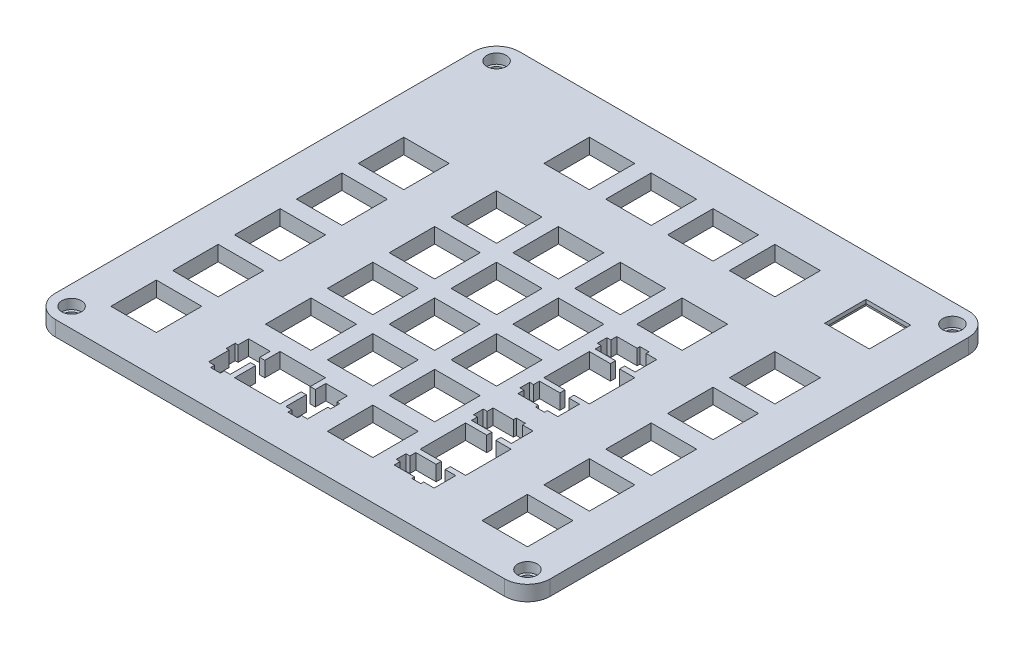
SolidWorks part; units mm, degrees
material "ABS"
ref_plane "Front Plane" through (0, 0, 0) normal (0, 0, 1) x (1, 0, 0)
ref_plane "Top Plane" through (0, 0, 0) normal (0, 1, 0) x (1, 0, 0)
ref_plane "Right Plane" through (0, 0, 0) normal (1, 0, 0) x (0, 0, -1)
sketch "Sketch6" plane through (0, 0, 0) normal (0, 1, 0) x (1, 0, 0)
  line L0 (7, 0) -> (145.39, 0)
  line L1 (152.39, 7) -> (152.39, 135.87)
  line L2 (7, 142.87) -> (145.39, 142.87)
  line L3 (0, 135.87) -> (0, 7)
  line L4 (54.62, 130.825) -> (40.62, 130.825)
  line L5 (40.62, 130.825) -> (40.62, 116.825)
  line L6 (40.62, 116.825) -> (54.62, 116.825)
  line L7 (54.62, 116.825) -> (54.62, 130.825)
  line L8 (73.67, 130.825) -> (59.67, 130.825)
  line L9 (59.67, 130.825) -> (59.67, 116.825)
  line L10 (59.67, 116.825) -> (73.67, 116.825)
  line L11 (73.67, 116.825) -> (73.67, 130.825)
  line L12 (92.72, 130.825) -> (78.72, 130.825)
  line L13 (78.72, 130.825) -> (78.72, 116.825)
  line L14 (78.72, 116.825) -> (92.72, 116.825)
  line L15 (92.72, 116.825) -> (92.72, 130.825)
  line L16 (111.77, 130.825) -> (97.77, 130.825)
  line L17 (97.77, 130.825) -> (97.77, 116.825)
  line L18 (97.77, 116.825) -> (111.77, 116.825)
  line L19 (111.77, 116.825) -> (111.77, 130.825)
  line L20 (26.045, 102.25) -> (12.045, 102.25)
  line L21 (12.045, 102.25) -> (12.045, 88.25)
  line L22 (12.045, 88.25) -> (26.045, 88.25)
  line L23 (26.045, 88.25) -> (26.045, 102.25)
  line L24 (54.62, 102.25) -> (40.62, 102.25)
  line L25 (40.62, 102.25) -> (40.62, 88.25)
  line L26 (40.62, 88.25) -> (54.62, 88.25)
  line L27 (54.62, 88.25) -> (54.62, 102.25)
  line L28 (73.67, 102.25) -> (59.67, 102.25)
  line L29 (59.67, 102.25) -> (59.67, 88.25)
  line L30 (59.67, 88.25) -> (73.67, 88.25)
  line L31 (73.67, 88.25) -> (73.67, 102.25)
  line L32 (92.72, 102.25) -> (78.72, 102.25)
  line L33 (78.72, 102.25) -> (78.72, 88.25)
  line L34 (78.72, 88.25) -> (92.72, 88.25)
  line L35 (92.72, 88.25) -> (92.72, 102.25)
  line L36 (111.77, 102.25) -> (97.77, 102.25)
  line L37 (97.77, 102.25) -> (97.77, 88.25)
  line L38 (97.77, 88.25) -> (111.77, 88.25)
  line L39 (111.77, 88.25) -> (111.77, 102.25)
  line L40 (140.345, 102.25) -> (126.345, 102.25)
  line L41 (126.345, 102.25) -> (126.345, 88.25)
  line L42 (126.345, 88.25) -> (140.345, 88.25)
  line L43 (140.345, 88.25) -> (140.345, 102.25)
  line L44 (26.045, 83.2) -> (12.045, 83.2)
  line L45 (12.045, 83.2) -> (12.045, 69.2)
  line L46 (12.045, 69.2) -> (26.045, 69.2)
  line L47 (26.045, 69.2) -> (26.045, 83.2)
  line L48 (54.62, 83.2) -> (40.62, 83.2)
  line L49 (40.62, 83.2) -> (40.62, 69.2)
  line L50 (40.62, 69.2) -> (54.62, 69.2)
  line L51 (54.62, 69.2) -> (54.62, 83.2)
  line L52 (73.67, 83.2) -> (59.67, 83.2)
  line L53 (59.67, 83.2) -> (59.67, 69.2)
  line L54 (59.67, 69.2) -> (73.67, 69.2)
  line L55 (73.67, 69.2) -> (73.67, 83.2)
  line L56 (92.72, 83.2) -> (78.72, 83.2)
  line L57 (78.72, 83.2) -> (78.72, 69.2)
  line L58 (78.72, 69.2) -> (92.72, 69.2)
  line L59 (92.72, 69.2) -> (92.72, 83.2)
  line L60 (98, 77.075) -> (98, 75.25)
  line L61 (98, 75.25) -> (104.27, 75.25)
  line L62 (104.27, 75.25) -> (104.27, 73.675)
  line L63 (104.27, 73.675) -> (97.77, 73.675)
  line L64 (97.77, 73.675) -> (97.77, 59.675)
  line L65 (97.77, 59.675) -> (104.27, 59.675)
  line L66 (104.27, 59.675) -> (104.27, 58.1)
  line L67 (104.27, 58.1) -> (98, 58.1)
  line L68 (98, 58.1) -> (98, 56.275)
  line L69 (98, 56.275) -> (96.8, 56.275)
  line L70 (96.8, 56.275) -> (96.8, 53.275)
  line L71 (96.8, 53.275) -> (98, 53.275)
  line L72 (98, 53.275) -> (98, 51.45)
  line L73 (98, 51.45) -> (104.27, 51.45)
  line L74 (104.27, 51.45) -> (104.27, 50.575)
  line L75 (104.27, 50.575) -> (107.07, 50.575)
  line L76 (107.07, 50.575) -> (107.07, 51.45)
  line L77 (107.07, 51.45) -> (110.3, 51.45)
  line L78 (110.3, 51.45) -> (110.3, 58.1)
  line L79 (110.3, 58.1) -> (107.07, 58.1)
  line L80 (107.07, 58.1) -> (107.07, 59.675)
  line L81 (107.07, 59.675) -> (111.77, 59.675)
  line L82 (111.77, 59.675) -> (111.77, 73.675)
  line L83 (111.77, 73.675) -> (107.07, 73.675)
  line L84 (107.07, 73.675) -> (107.07, 75.25)
  line L85 (107.07, 75.25) -> (110.3, 75.25)
  line L86 (110.3, 75.25) -> (110.3, 81.9)
  line L87 (110.3, 81.9) -> (107.07, 81.9)
  line L88 (107.07, 81.9) -> (107.07, 82.775)
  line L89 (107.07, 82.775) -> (104.27, 82.775)
  line L90 (104.27, 82.775) -> (104.27, 81.9)
  line L91 (104.27, 81.9) -> (98, 81.9)
  line L92 (98, 81.9) -> (98, 80.075)
  line L93 (98, 80.075) -> (96.8, 80.075)
  line L94 (96.8, 80.075) -> (96.8, 77.075)
  line L95 (96.8, 77.075) -> (98, 77.075)
  line L96 (140.345, 83.2) -> (126.345, 83.2)
  line L97 (126.345, 83.2) -> (126.345, 69.2)
  line L98 (126.345, 69.2) -> (140.345, 69.2)
  line L99 (140.345, 69.2) -> (140.345, 83.2)
  line L100 (26.045, 64.15) -> (12.045, 64.15)
  line L101 (12.045, 64.15) -> (12.045, 50.15)
  line L102 (12.045, 50.15) -> (26.045, 50.15)
  line L103 (26.045, 50.15) -> (26.045, 64.15)
  line L104 (54.62, 64.15) -> (40.62, 64.15)
  line L105 (40.62, 64.15) -> (40.62, 50.15)
  line L106 (40.62, 50.15) -> (54.62, 50.15)
  line L107 (54.62, 50.15) -> (54.62, 64.15)
  line L108 (73.67, 64.15) -> (59.67, 64.15)
  line L109 (59.67, 64.15) -> (59.67, 50.15)
  line L110 (59.67, 50.15) -> (73.67, 50.15)
  line L111 (73.67, 50.15) -> (73.67, 64.15)
  line L112 (92.72, 64.15) -> (78.72, 64.15)
  line L113 (78.72, 64.15) -> (78.72, 50.15)
  line L114 (78.72, 50.15) -> (92.72, 50.15)
  line L115 (92.72, 50.15) -> (92.72, 64.15)
  line L116 (140.345, 64.15) -> (126.345, 64.15)
  line L117 (126.345, 64.15) -> (126.345, 50.15)
  line L118 (126.345, 50.15) -> (140.345, 50.15)
  line L119 (140.345, 50.15) -> (140.345, 64.15)
  line L120 (26.045, 45.1) -> (12.045, 45.1)
  line L121 (12.045, 45.1) -> (12.045, 31.1)
  line L122 (12.045, 31.1) -> (26.045, 31.1)
  line L123 (26.045, 31.1) -> (26.045, 45.1)
  line L124 (54.62, 45.1) -> (40.62, 45.1)
  line L125 (40.62, 45.1) -> (40.62, 31.1)
  line L126 (40.62, 31.1) -> (54.62, 31.1)
  line L127 (54.62, 31.1) -> (54.62, 45.1)
  line L128 (73.67, 45.1) -> (59.67, 45.1)
  line L129 (59.67, 45.1) -> (59.67, 31.1)
  line L130 (59.67, 31.1) -> (73.67, 31.1)
  line L131 (73.67, 31.1) -> (73.67, 45.1)
  line L132 (92.72, 45.1) -> (78.72, 45.1)
  line L133 (78.72, 45.1) -> (78.72, 31.1)
  line L134 (78.72, 31.1) -> (92.72, 31.1)
  line L135 (92.72, 31.1) -> (92.72, 45.1)
  line L136 (98, 38.975) -> (98, 37.15)
  line L137 (98, 37.15) -> (104.27, 37.15)
  line L138 (104.27, 37.15) -> (104.27, 35.575)
  line L139 (104.27, 35.575) -> (97.77, 35.575)
  line L140 (97.77, 35.575) -> (97.77, 21.575)
  line L141 (97.77, 21.575) -> (104.27, 21.575)
  line L142 (104.27, 21.575) -> (104.27, 20)
  line L143 (104.27, 20) -> (98, 20)
  line L144 (98, 20) -> (98, 18.175)
  line L145 (98, 18.175) -> (96.8, 18.175)
  line L146 (96.8, 18.175) -> (96.8, 15.175)
  line L147 (96.8, 15.175) -> (98, 15.175)
  line L148 (98, 15.175) -> (98, 13.35)
  line L149 (98, 13.35) -> (104.27, 13.35)
  line L150 (104.27, 13.35) -> (104.27, 12.475)
  line L151 (104.27, 12.475) -> (107.07, 12.475)
  line L152 (107.07, 12.475) -> (107.07, 13.35)
  line L153 (107.07, 13.35) -> (110.3, 13.35)
  line L154 (110.3, 13.35) -> (110.3, 20)
  line L155 (110.3, 20) -> (107.07, 20)
  line L156 (107.07, 20) -> (107.07, 21.575)
  line L157 (107.07, 21.575) -> (111.77, 21.575)
  line L158 (111.77, 21.575) -> (111.77, 35.575)
  line L159 (111.77, 35.575) -> (107.07, 35.575)
  line L160 (107.07, 35.575) -> (107.07, 37.15)
  line L161 (107.07, 37.15) -> (110.3, 37.15)
  line L162 (110.3, 37.15) -> (110.3, 43.8)
  line L163 (110.3, 43.8) -> (107.07, 43.8)
  line L164 (107.07, 43.8) -> (107.07, 44.675)
  line L165 (107.07, 44.675) -> (104.27, 44.675)
  line L166 (104.27, 44.675) -> (104.27, 43.8)
  line L167 (104.27, 43.8) -> (98, 43.8)
  line L168 (98, 43.8) -> (98, 41.975)
  line L169 (98, 41.975) -> (96.8, 41.975)
  line L170 (96.8, 41.975) -> (96.8, 38.975)
  line L171 (96.8, 38.975) -> (98, 38.975)
  line L172 (140.345, 45.1) -> (126.345, 45.1)
  line L173 (126.345, 45.1) -> (126.345, 31.1)
  line L174 (126.345, 31.1) -> (140.345, 31.1)
  line L175 (140.345, 31.1) -> (140.345, 45.1)
  line L176 (26.045, 26.05) -> (12.045, 26.05)
  line L177 (12.045, 26.05) -> (12.045, 12.05)
  line L178 (12.045, 12.05) -> (26.045, 12.05)
  line L179 (26.045, 12.05) -> (26.045, 26.05)
  line L180 (46.745, 12.28) -> (48.57, 12.28)
  line L181 (48.57, 12.28) -> (48.57, 18.55)
  line L182 (48.57, 18.55) -> (50.145, 18.55)
  line L183 (50.145, 18.55) -> (50.145, 12.05)
  line L184 (50.145, 12.05) -> (64.145, 12.05)
  line L185 (64.145, 12.05) -> (64.145, 18.55)
  line L186 (64.145, 18.55) -> (65.72, 18.55)
  line L187 (65.72, 18.55) -> (65.72, 12.28)
  line L188 (65.72, 12.28) -> (67.545, 12.28)
  line L189 (67.545, 12.28) -> (67.545, 11.08)
  line L190 (67.545, 11.08) -> (70.545, 11.08)
  line L191 (70.545, 11.08) -> (70.545, 12.28)
  line L192 (70.545, 12.28) -> (72.37, 12.28)
  line L193 (72.37, 12.28) -> (72.37, 18.55)
  line L194 (72.37, 18.55) -> (73.245, 18.55)
  line L195 (73.245, 18.55) -> (73.245, 21.35)
  line L196 (73.245, 21.35) -> (72.37, 21.35)
  line L197 (72.37, 21.35) -> (72.37, 24.58)
  line L198 (72.37, 24.58) -> (65.72, 24.58)
  line L199 (65.72, 24.58) -> (65.72, 21.35)
  line L200 (65.72, 21.35) -> (64.145, 21.35)
  line L201 (64.145, 21.35) -> (64.145, 26.05)
  line L202 (64.145, 26.05) -> (50.145, 26.05)
  line L203 (50.145, 26.05) -> (50.145, 21.35)
  line L204 (50.145, 21.35) -> (48.57, 21.35)
  line L205 (48.57, 21.35) -> (48.57, 24.58)
  line L206 (48.57, 24.58) -> (41.92, 24.58)
  line L207 (41.92, 24.58) -> (41.92, 21.35)
  line L208 (41.92, 21.35) -> (41.045, 21.35)
  line L209 (41.045, 21.35) -> (41.045, 18.55)
  line L210 (41.045, 18.55) -> (41.92, 18.55)
  line L211 (41.92, 18.55) -> (41.92, 12.28)
  line L212 (41.92, 12.28) -> (43.745, 12.28)
  line L213 (43.745, 12.28) -> (43.745, 11.08)
  line L214 (43.745, 11.08) -> (46.745, 11.08)
  line L215 (46.745, 11.08) -> (46.745, 12.28)
  line L216 (92.72, 26.05) -> (78.72, 26.05)
  line L217 (78.72, 26.05) -> (78.72, 12.05)
  line L218 (78.72, 12.05) -> (92.72, 12.05)
  line L219 (92.72, 12.05) -> (92.72, 26.05)
  line L220 (140.345, 26.05) -> (126.345, 26.05)
  line L221 (126.345, 26.05) -> (126.345, 12.05)
  line L222 (126.345, 12.05) -> (140.345, 12.05)
  line L223 (140.345, 12.05) -> (140.345, 26.05)
  line L224 (135.34, 123.82) -> (131.34, 123.82) construction
  line L225 (133.34, 121.82) -> (133.34, 125.82) construction
  line L228 (76.195, 0) -> (76.195, 142.87) construction
  line L229 (0, 71.435) -> (152.39, 71.435) construction
  line L230 (5.995, 134.725) -> (5.995, 139.025) construction
  line L231 (8.145, 136.875) -> (3.845, 136.875) construction
  line L232 (144.245, 136.875) -> (148.545, 136.875) construction
  line L233 (146.395, 134.725) -> (146.395, 139.025) construction
  line L234 (144.245, 5.995) -> (148.545, 5.995) construction
  line L235 (146.395, 8.145) -> (146.395, 3.845) construction
  line L236 (8.145, 5.995) -> (3.845, 5.995) construction
  line L237 (5.995, 8.145) -> (5.995, 3.845) construction
  circle A0 centre (19.045, 19.05) radius 2
  circle A1 centre (19.045, 38.1) radius 2
  circle A2 centre (19.045, 57.15) radius 2
  circle A4 centre (19.045, 76.2) radius 2
  circle A5 centre (19.045, 95.25) radius 2
  circle A6 centre (85.72, 95.25) radius 2
  circle A7 centre (85.72, 57.15) radius 2
  circle A8 centre (85.72, 76.2) radius 2
  circle A9 centre (85.72, 19.05) radius 2
  circle A10 centre (85.72, 38.1) radius 2
  circle A11 centre (133.345, 19.05) radius 2
  circle A12 centre (133.345, 95.25) radius 2
  circle A13 centre (133.345, 38.1) radius 2
  circle A14 centre (133.345, 57.15) radius 2
  circle A15 centre (133.345, 76.2) radius 2
  circle A16 centre (66.67, 57.15) radius 2
  circle A17 centre (66.67, 76.2) radius 2
  circle A18 centre (66.67, 95.25) radius 2
  circle A19 centre (66.67, 38.1) radius 2
  circle A20 centre (47.62, 95.25) radius 2
  circle A21 centre (47.62, 76.2) radius 2
  circle A22 centre (47.62, 38.1) radius 2
  circle A23 centre (47.62, 57.15) radius 2
  circle A24 centre (104.77, 95.25) radius 2
  circle A25 centre (66.67, 123.825) radius 2
  circle A26 centre (85.72, 123.825) radius 2
  circle A27 centre (104.77, 123.825) radius 2
  circle A28 centre (47.62, 123.825) radius 2
  circle A29 centre (57.145, 19.05) radius 2
  circle A30 centre (104.77, 28.575) radius 2
  circle A31 centre (104.77, 66.675) radius 2
  arc A32 (145.39, 0) -> (152.39, 7) centre (145.39, 7) ccw
  arc A33 (7, 0) -> (0, 7) centre (7, 7) cw
  arc A34 (7, 142.87) -> (0, 135.87) centre (7, 135.87) ccw
  arc A35 (152.39, 135.87) -> (145.39, 142.87) centre (145.39, 135.87) ccw
  circle A37 centre (133.34, 123.82) radius 2
  circle A38 centre (5.995, 136.875) radius 2.15
  circle A39 centre (146.395, 136.875) radius 2.15
  circle A40 centre (146.395, 5.995) radius 2.15
  circle A41 centre (5.995, 5.995) radius 2.15
  point P289 (152.39, 0)
  point P292 (0, 0)
  point P295 (0, 142.87)
  dimension "D4" = 4
  dimension "D5" = 7
  dimension "D11" = 4
  dimension "D12" = 4.3
  dimension "D1" = 14
  dimension "D2" = 152.39
  dimension "D3" = 142.87
  dimension "D9" = 19.05
  dimension "D10" = 19.05
  dimension "D13" = 70.2
  dimension "D14" = 65.44
sketch "Sketch8" [suppressed] plane through (0, 0, 0) normal (0, 1, 0) x (1, 0, 0)
  line L0 (7, 0) -> (145.39, 0)
  line L1 (152.39, 7) -> (152.39, 135.87)
  line L2 (7, 142.87) -> (145.39, 142.87)
  line L3 (0, 135.87) -> (0, 7)
  arc A32 (145.39, 0) -> (152.39, 7) centre (145.39, 7) ccw
  arc A33 (7, 0) -> (0, 7) centre (7, 7) cw
  arc A34 (7, 142.87) -> (0, 135.87) centre (7, 135.87) ccw
  arc A35 (152.39, 135.87) -> (145.39, 142.87) centre (145.39, 135.87) ccw
extrude "Boss-Extrude1" add sketch "Sketch6" along normal blind 4.68
sketch "Sketch15" plane through (0, 4.68, 0) normal (0, 1, 0) x (1, 0, 0)
  line L1 (126.465, 130.195) -> (140.215, 130.195)
  line L2 (126.465, 130.195) -> (126.465, 117.445)
  line L3 (126.465, 117.445) -> (140.215, 117.445)
  line L4 (140.215, 130.195) -> (140.215, 117.445)
  line L5 (126.465, 130.195) -> (140.215, 117.445) construction
  line L6 (126.465, 117.445) -> (140.215, 130.195) construction
  point P0 (133.34, 123.82)
  dimension "D1" = 13.75
  dimension "D2" = 12.75
extrude "Cut-Extrude1" cut sketch "Sketch15" against normal through all both and the other way through all
sketch "Sketch16" plane through (0, 0, 0) normal (0, -1, 0) x (1, 0, 0)
  line L0 (11.45, -119.58) -> (11.45, -123.58) construction
  line L1 (17.9, -119.58) -> (17.9, -123.58)
  line L2 (5, -119.58) -> (5, -123.58)
  line L4 (0, -135.87) -> (0, -7) construction
  line L5 (7, -142.87) -> (145.39, -142.87) construction
  arc A0 (17.9, -119.58) -> (5, -119.58) centre (11.45, -119.58) ccw
  arc A1 (5, -123.58) -> (17.9, -123.58) centre (11.45, -123.58) ccw
  point P2 (11.45, -121.58)
  dimension "D1" = 21.29
  dimension "D2" = 4
  dimension "D3" = 5
  dimension "D4" = 12.9
extrude "Cut-Extrude2" cut sketch "Sketch16" against normal blind 2
sketch "Sketch17" plane through (0, 4.68, 0) normal (0, 1, 0) x (1, 0, 0)
  circle A0 centre (5.995, 136.875) radius 3
  circle A1 centre (146.395, 136.875) radius 3
  circle A2 centre (146.395, 5.995) radius 3
  circle A3 centre (5.995, 5.995) radius 3
  dimension "D1" = 6
  dimension "D2" = 6
  dimension "D3" = 6
  dimension "D4" = 6
extrude "Cut-Extrude3" cut sketch "Sketch17" against normal blind 3 contours A3 | A2 | A1 | A0
sketch "Sketch19" plane through (0, 0, 0) normal (0, -1, 0) x (1, 0, 0)
  line L0 (126.465, -130.195) -> (140.215, -117.445) construction
  line L1 (126.465, -117.445) -> (140.215, -130.195) construction
  line L2 (140.215, -117.445) -> (140.215, -130.195) construction
  line L3 (123.465, -114.445) -> (143.215, -114.445)
  line L4 (123.465, -114.445) -> (123.465, -133.195)
  line L5 (123.465, -133.195) -> (143.215, -133.195)
  line L6 (143.215, -114.445) -> (143.215, -133.195)
  line L7 (123.465, -114.445) -> (143.215, -133.195) construction
  line L8 (123.465, -133.195) -> (143.215, -114.445) construction
  line L9 (140.215, -130.195) -> (126.465, -130.195) construction
  point P8 (133.34, -123.82)
  dimension "D1" = 3
  dimension "D2" = 3
extrude "Cut-Extrude5" cut sketch "Sketch19" against normal blind 3.5
sketch "Sketch18" plane through (0, 0, 0) normal (0, -1, 0) x (1, 0, 0)
  line L0 (7, -142.87) -> (145.39, -142.87) construction
  line L1 (28.35, -134.44) -> (40.49, -134.44)
  line L2 (28.35, -134.44) -> (28.35, -142.87)
  line L3 (28.35, -142.87) -> (40.49, -142.87)
  line L4 (40.49, -134.44) -> (40.49, -142.87)
  line L5 (28.35, -134.44) -> (40.49, -142.87) construction
  line L6 (28.35, -142.87) -> (40.49, -134.44) construction
  line L8 (0, -135.87) -> (0, -7) construction
  point P0 (34.42, -138.655)
  dimension "D1" = 34.42
  dimension "D2" = 8.43
  dimension "D3" = 12.14
extrude "Cut-Extrude4" cut sketch "Sketch18" against normal blind 2
